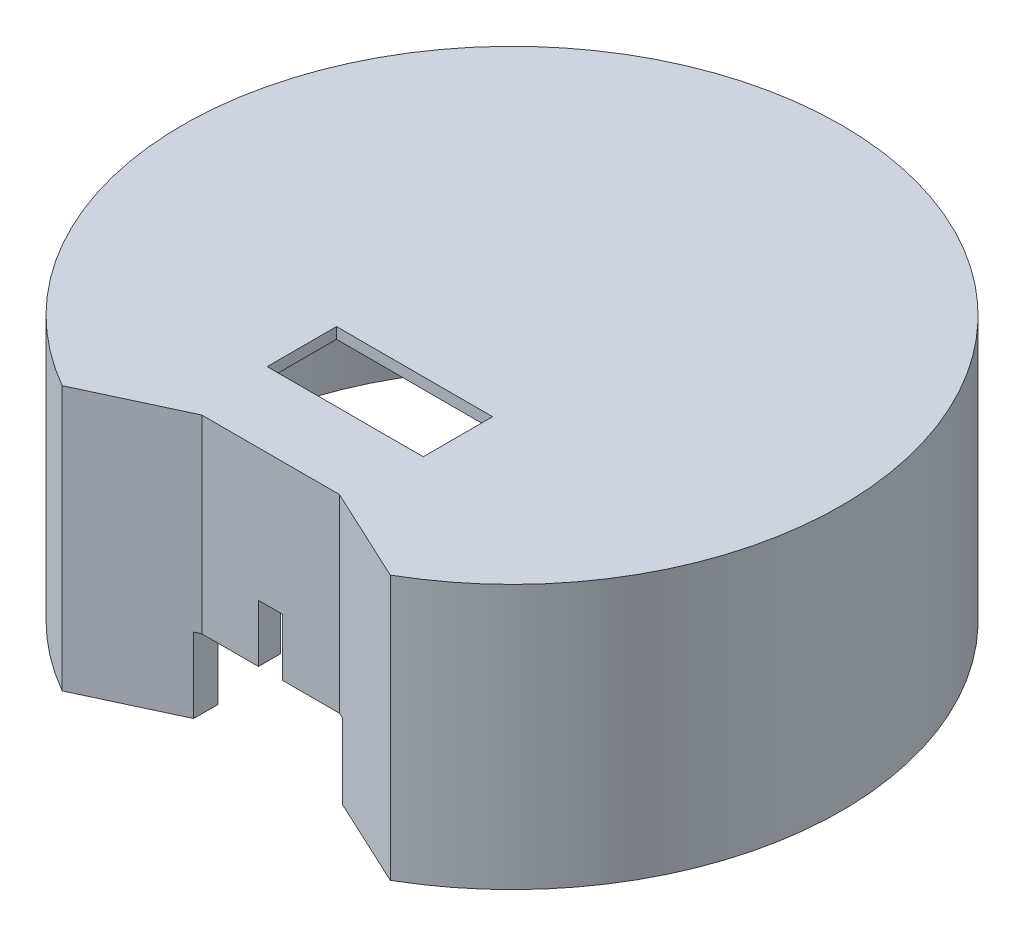
SolidWorks part; units mm, degrees
material "PE High Density"
ref_plane "Front Plane" through (0, 0, 0) normal (0, 0, 1) x (1, 0, 0)
ref_plane "Top Plane" through (0, 0, 0) normal (0, 1, 0) x (1, 0, 0)
ref_plane "Right Plane" through (0, 0, 0) normal (1, 0, 0) x (0, 0, -1)
sketch "Sketch1" plane through (0, 0, 0) normal (0, 1, 0) x (1, 0, 0)
  line L0 (-39.6875, -139.2) -> (39.6875, -139.2)
  line L1 (39.6875, -139.2) -> (94.5702, -164.7922)
  line L2 (-39.6875, -139.2) -> (-94.5702, -164.7922)
  line L3 (-209.8695, -190) -> (261.5237, -190) construction
  circle A0 centre (0, 0) radius 190 construction
  arc A1 (-94.5702, -164.7922) -> (94.5702, -164.7922) centre (0, 0) cw
  dimension "D1" = 380
  dimension "D2" = 155
  dimension "D3" = 79.375
  dimension "D4" = 155
  dimension "D5" = 50.8
extrude "Boss-Extrude1" add sketch "Sketch1" along normal blind 152.4
shell "Shell2" thickness 12.7
sketch "Sketch2" plane through (0, 0, 0) normal (0, -1, 0) x (1, 0, 0)
  line L2 (-42.503, 126.5) -> (42.503, 126.5)
  line L3 (-39.6875, 139.2) -> (-94.5702, 164.7922)
  line L4 (94.5702, 164.7922) -> (39.6875, 139.2)
  line L5 (39.6875, 139.2) -> (-39.6875, 139.2)
  line L6 (-39.6875, 139.2) -> (-94.5702, 164.7922) construction
  line L7 (94.5702, 164.7922) -> (39.6875, 139.2) construction
  line L8 (39.6875, 139.2) -> (-39.6875, 139.2)
  line L10 (-42.8625, 140.6805) -> (-39.6875, 139.2)
  line L12 (42.8625, 140.6805) -> (39.6875, 139.2)
  line L13 (-42.8625, 126.6676) -> (-42.8625, 140.6805)
  line L14 (-93.8324, 150.4353) -> (-42.503, 126.5) construction
  line L15 (42.8625, 140.6805) -> (42.8625, 126.6676)
  line L16 (42.503, 126.5) -> (93.8324, 150.4353) construction
  line L17 (-42.503, 126.5) -> (-42.8625, 126.6676)
  line L18 (42.503, 126.5) -> (42.8625, 126.6676)
  arc A1 (-94.5702, 164.7922) -> (94.5702, 164.7922) centre (0, 0) ccw
  arc A2 (-94.5702, 164.7922) -> (94.5702, 164.7922) centre (0, 0) ccw construction
  dimension "D2" = 85.725
  dimension "D1" = 0
extrude "Cut-Extrude1" cut sketch "Sketch2" against normal blind 43.175
sketch "Sketch3" plane through (0, 152.4, 0) normal (0, 1, 0) x (1, 0, 0)
  line L0 (0, -96.2) -> (0, -139.2) construction
  line L1 (-45, -96.2) -> (45, -96.2)
  line L2 (-45, -96.2) -> (-45, -56.2)
  line L3 (-45, -56.2) -> (45, -56.2)
  line L4 (45, -96.2) -> (45, -56.2)
  line L5 (-39.6875, -139.2) -> (39.6875, -139.2) construction
  dimension "D1" = 43
  dimension "D2" = 40
  dimension "D3" = 90
extrude "Cut-Extrude2" cut sketch "Sketch3" against normal through all both and the other way through all
sketch "Sketch4" plane through (0, 0, 139.2) normal (0, 0, 1) x (1, 0, 0)
  line L0 (0, 43.175) -> (0, 109.225) construction
  line L1 (-39.6875, 25.4) -> (39.6875, 25.4) construction
  line L2 (-6.985, 76.2) -> (6.985, 76.2)
  line L3 (-6.985, 76.2) -> (-6.985, 43.175)
  line L4 (-39.6875, 152.4) -> (-39.6875, 43.175)
  line L5 (-39.6875, 43.175) -> (39.6875, 43.175)
  line L6 (39.6875, 43.175) -> (39.6875, 152.4)
  line L7 (39.6875, 152.4) -> (-39.6875, 152.4)
  line L8 (-39.6875, 152.4) -> (-39.6875, 43.175)
  line L9 (-39.6875, 43.175) -> (39.6875, 43.175)
  line L10 (39.6875, 43.175) -> (39.6875, 152.4)
  line L11 (39.6875, 152.4) -> (-39.6875, 152.4)
  line L12 (-6.985, 43.175) -> (6.985, 43.175)
  line L13 (6.985, 76.2) -> (6.985, 43.175)
  line L14 (-94.5702, 0) -> (-42.8625, 0) construction
  point P11 (0, 76.2)
  line M9 (-39.6875, 43.175) -> (39.6875, 43.175)
  dimension "D2" = 13.97
  dimension "D3" = 25.4
  dimension "D4" = 50.8
  dimension "D1" = 0
extrude "Cut-Extrude3" cut sketch "Sketch4" against normal up to surface (12.7 mm away) contours L13 L2 L3 M9 up to face at (0, 91.4375, 126.5)
sketch "Sketch5" plane through (0, 139.7, 0) normal (0, -1, 0) x (1, 0, 0)
  line L3 (-42.503, 126.5) -> (-93.8324, 150.4353)
  line L4 (93.8324, 150.4353) -> (42.503, 126.5)
  line L5 (42.503, 126.5) -> (-42.503, 126.5)
  line L6 (-42.503, 126.5) -> (-93.8324, 150.4353)
  line L7 (93.8324, 150.4353) -> (42.503, 126.5)
  line L8 (42.503, 126.5) -> (-42.503, 126.5)
  arc A1 (-93.8324, 150.4353) -> (93.8324, 150.4353) centre (0, 0) ccw
  arc A2 (-93.8324, 150.4353) -> (93.8324, 150.4353) centre (0, 0) ccw
  line M5 (-45, 56.2) -> (-45, 96.2)
  line M6 (-45, 96.2) -> (45, 96.2)
  line M7 (45, 96.2) -> (45, 56.2)
  line M8 (45, 56.2) -> (-45, 56.2)
  line M9 (-42.503, 126.5) -> (-93.8324, 150.4353)
  arc M10 (-93.8324, 150.4353) -> (93.8324, 150.4353) centre (0, 0) ccw
  line M11 (93.8324, 150.4353) -> (42.503, 126.5)
  line M12 (42.503, 126.5) -> (-42.503, 126.5)
  dimension "D1" = 0
extrude "Cut-Extrude4" cut sketch "Sketch5" against normal blind 6.35 contours M12 M9 M10 M11 M8 M5 M6 M7
